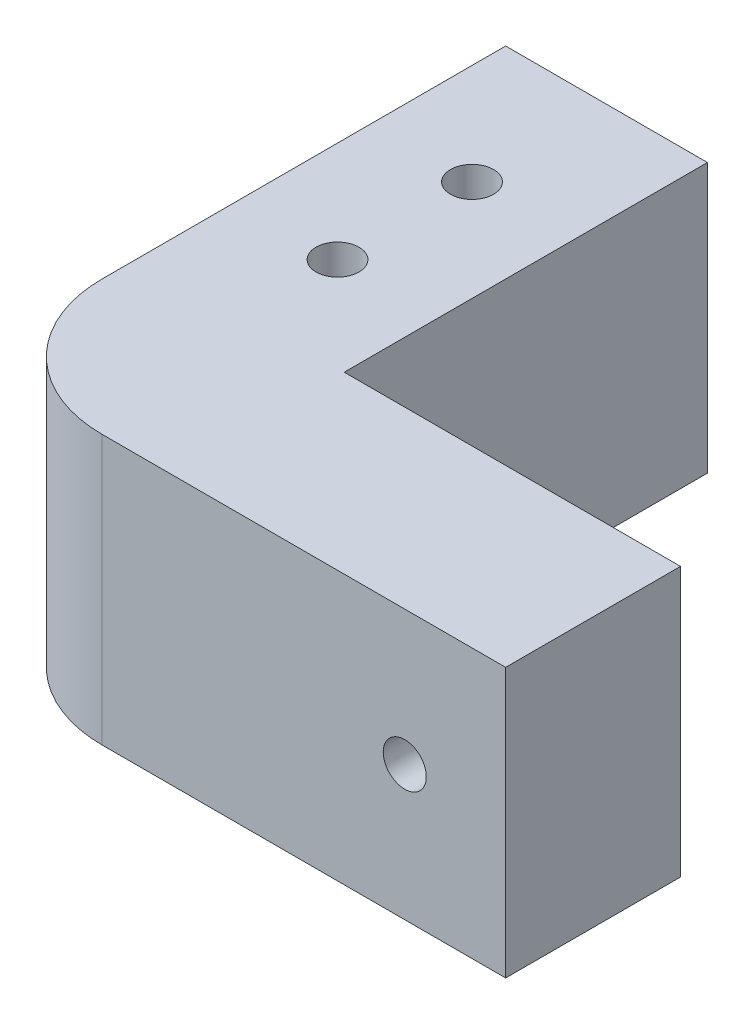
SolidWorks part; units mm, degrees
material "ABS"
ref_plane "前视基准面" through (0, 0, 0) normal (0, 0, 1) x (1, 0, 0)
ref_plane "上视基准面" through (0, 0, 0) normal (0, 1, 0) x (1, 0, 0)
ref_plane "右视基准面" through (0, 0, 0) normal (1, 0, 0) x (0, 0, -1)
other "Configuration Table"
sketch "草图1" plane through (0, 0, 0) normal (0, 1, 0) x (1, 0, 0)
  line L0 (7.5, 36.6638) -> (7.5, -9.8863) construction
  line L1 (0, 0) -> (40, 0)
  line L2 (0, 0) -> (0, 40)
  line L3 (0, 40) -> (40, 40)
  line L4 (40, 0) -> (40, 40)
  circle A0 centre (7.5, 30) radius 1.6
  circle A1 centre (7.5, 20) radius 1.6
  dimension "D4" = 10
  dimension "D5" = 3.2
  dimension "D1" = 40
  dimension "D2" = 7.5
  dimension "D3" = 10
extrude "凸台-拉伸1" add sketch "草图1" along normal blind 20
sketch "草图2" plane through (0, 0, -40) normal (0, 0, -1) x (-1, 0, 0)
  line L0 (-31.9002, 10) -> (1.5699, 10) construction
  line L1 (0, 20) -> (0, 0) construction
  line L2 (-40, 20) -> (-40, 0) construction
  circle A0 centre (-32.5, 10) radius 1.6
  point P4 (0, 10)
  dimension "D1" = 3.2
  dimension "D2" = 7.5
extrude "切除-拉伸1" cut sketch "草图2" against normal through all
sketch "草图3" plane through (0, 0, -40) normal (0, 0, -1) x (-1, 0, 0)
  line L0 (-40, 0) -> (0, 0) construction
  line L1 (-40, 20) -> (-15, 20)
  line L2 (-40, 20) -> (-40, 0)
  line L3 (-40, 0) -> (-15, 0)
  line L4 (-15, 20) -> (-15, 0)
  line L5 (0, 20) -> (0, 0) construction
  dimension "D1" = 15
extrude "切除-拉伸2" cut sketch "草图3" against normal blind 27
fillet "圆角1" radius 10 1 edges at (0, 10, 0)
